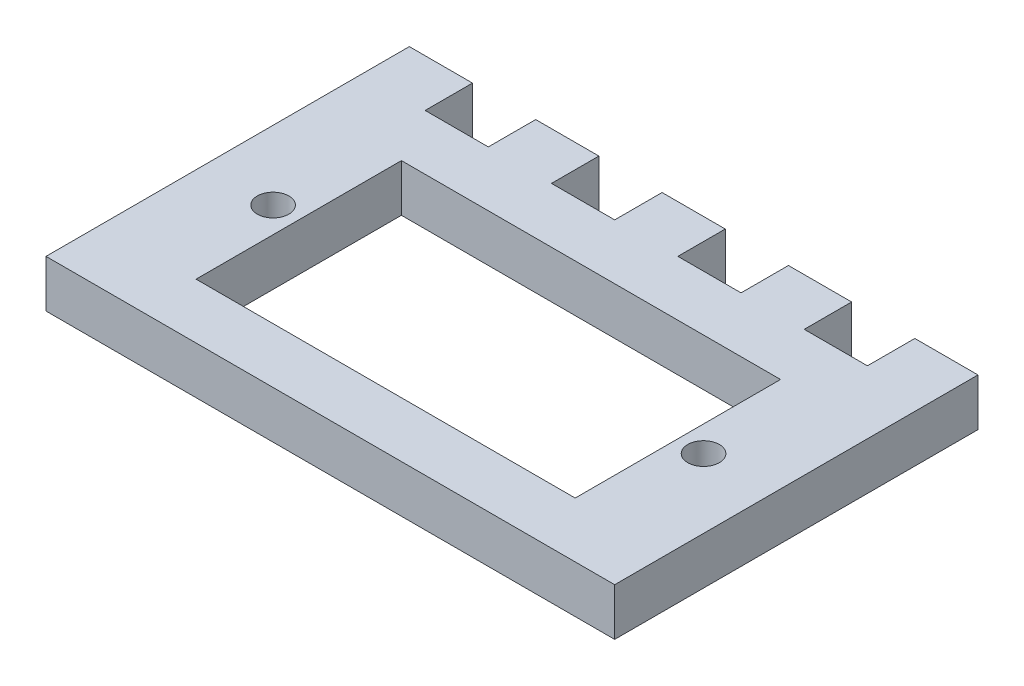
SolidWorks part; units mm, degrees
ref_plane "Front Plane" through (0, 0, 0) normal (0, 0, 1) x (1, 0, 0)
ref_plane "Top Plane" through (0, 0, 0) normal (0, 1, 0) x (1, 0, 0)
ref_plane "Right Plane" through (0, 0, 0) normal (1, 0, 0) x (0, 0, -1)
sketch "Sketch1" plane through (0, 0, 0) normal (0, 1, 0) x (1, 0, 0)
  line L0 (0, 0) -> (0, -6.7691) construction
  line L1 (-18, -10) -> (18, -10)
  line L2 (-18, -10) -> (-18, 10)
  line L4 (18, -10) -> (18, 10)
  line L5 (-18, -10) -> (18, 10) construction
  line L6 (-18, 10) -> (18, -10) construction
  line L7 (-12, -6.5) -> (12, -6.5)
  line L8 (-12, -6.5) -> (-12, 6.5)
  line L9 (-12, 6.5) -> (12, 6.5)
  line L10 (12, -6.5) -> (12, 6.5)
  line L11 (-12, -6.5) -> (12, 6.5) construction
  line L12 (-12, 6.5) -> (12, -6.5) construction
  line L13 (-18, 10) -> (-18, 13)
  line L14 (-18, 13) -> (-14, 13)
  line L15 (-14, 13) -> (-14, 10)
  line L16 (-14, 10) -> (-10, 10)
  line L17 (-10, 10) -> (-10, 13)
  line L18 (-10, 13) -> (-6, 13)
  line L19 (-6, 13) -> (-6, 10)
  line L20 (-6, 10) -> (-2, 10)
  line L21 (-2, 10) -> (-2, 13)
  line L22 (-2, 13) -> (2, 13)
  line L23 (2, 13) -> (2, 10)
  line L24 (2, 10) -> (6, 10)
  line L25 (6, 10) -> (6, 13)
  line L26 (6, 13) -> (10, 13)
  line L27 (10, 13) -> (10, 10)
  line L28 (10, 10) -> (14, 10)
  line L29 (14, 10) -> (14, 13)
  line L30 (14, 13) -> (18, 13)
  line L31 (18, 13) -> (18, 10)
  circle A0 centre (-13.625, 0) radius 1
  circle A1 centre (13.625, 0) radius 1
  point P0 (0, 0)
  point P6 (0, 0)
  dimension "D2" = 2
  dimension "D1" = 24
  dimension "D3" = 27.25
  dimension "D4" = 36
  dimension "D5" = 20
  dimension "D6" = 13
  dimension "D7" = 3
extrude "Boss-Extrude1" add sketch "Sketch1" along normal blind 3
